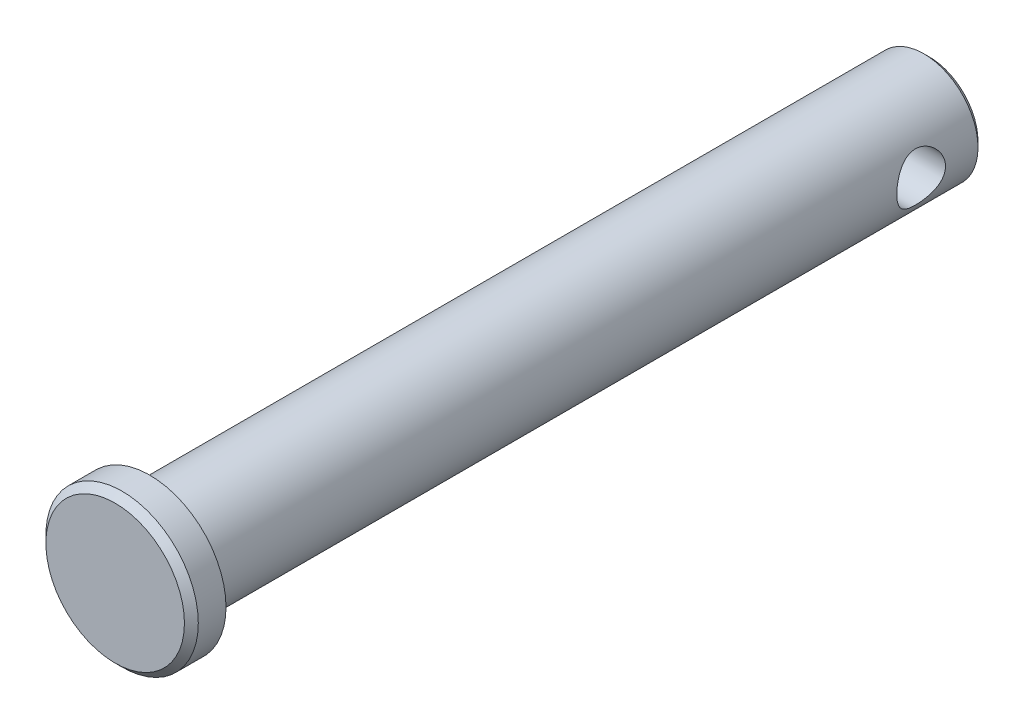
SolidWorks part; units mm, degrees
material "Alloy Steel"
ref_plane "Front" through (0, 0, 0) normal (0, 0, 1) x (1, 0, 0)
ref_plane "Top" through (0, 0, 0) normal (0, 1, 0) x (1, 0, 0)
ref_plane "Right" through (0, 0, 0) normal (1, 0, 0) x (0, 0, -1)
sketch "Sketch1" plane through (0, 0, 0) normal (0, 0, 1) x (1, 0, 0)
  circle A0 centre (0, 0) radius 3.9688
  point P3 (0, 3.9688)
  point P4 (0, -3.9688)
  dimension "dia" = 7.9375
extrude "Extrude1" add sketch "Sketch1" along normal mid plane 57.15
sketch "Sketch2" plane through (0, 0, 28.575) normal (0, 0, 1) x (1, 0, 0)
  circle A0 centre (0, 0) radius 5.588
  dimension "head dia" = 11.176
extrude "Extrude2" add sketch "Sketch2" along normal blind 2.54
chamfer "Chamfer1" distance 0.508 angle 45 1 edges at (5.588, 0, 31.115)
sketch "Sketch3" plane through (0, 0, 0) normal (1, 0, 0) x (0, 0, -1)
  line L0 (-28.575, -3.9688) -> (-28.575, 3.9688) construction
  circle A0 centre (24.0109, 0) radius 1.7859
  point P2 (22.225, 0)
  dimension "hole dia" = 3.5719
  dimension "useable Lg" = 50.8
extrude "Extrude3" cut sketch "Sketch3" against normal through all and the other way through all
chamfer "Chamfer2" distance 0.3969 angle 45 1 edges at (3.9688, 0, -28.575)
ref_plane "Plane1" [suppressed] through (0, 0, -24.0109) normal (0, 0, 1) x (1, 0, 0)
sketch "Sketch8" [suppressed] plane through (0, 0, 0) normal (1, 0, 0) x (0, 0, -1)
  line L0 (-31.115, 5.08) -> (-31.115, -5.08) construction
  line L1 (-30.607, -5.588) -> (-28.575, -5.588) construction
  line L2 (28.575, -3.5719) -> (28.575, 3.5719) construction
  point P0 (-31.115, 5.588)
  point P1 (-28.575, 5.588)
  point P5 (28.575, 3.9688)
  point P8 (-31.115, -5.588)
  point P9 (28.575, -3.9688)
equation "\"D1@Chamfer1\" = \"head ht@Extrude2\" * .2"
equation "\"D1@Chamfer2\" = \"dia@Sketch1\" * .05"
